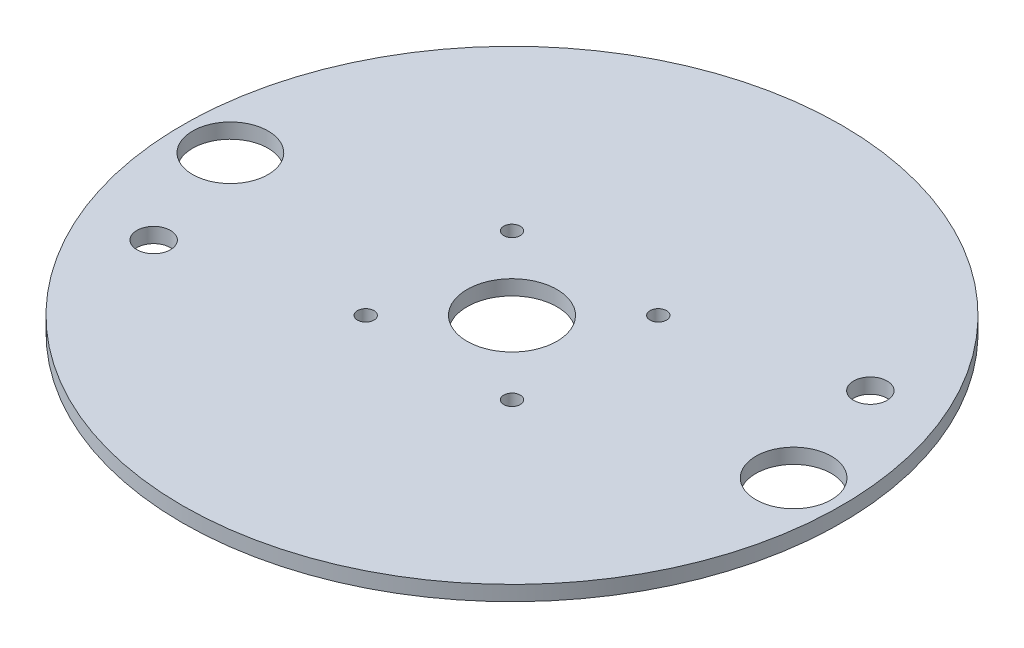
SolidWorks part; units mm, degrees
ref_plane "Front Plane" through (0, 0, 0) normal (0, 0, 1) x (1, 0, 0)
ref_plane "Top Plane" through (0, 0, 0) normal (0, 1, 0) x (1, 0, 0)
ref_plane "Right Plane" through (0, 0, 0) normal (1, 0, 0) x (0, 0, -1)
sketch "Sketch1" plane through (0, 0, 0) normal (0, 1, 0) x (1, 0, 0)
  circle A0 centre (0, 0) radius 69.85
  circle A1 centre (0, 0) radius 9.525
extrude "Boss-Extrude1" add sketch "Sketch1" along normal blind 3.175
sketch "Sketch2" plane through (0, 3.175, 0) normal (0, 1, 0) x (1, 0, 0)
  line L0 (59.69, 0) -> (-59.69, 0) construction
  line L1 (51.7955, 24.1526) -> (-51.7955, -24.1526) construction
  circle A0 centre (-59.69, 0) radius 8.001
  circle A1 centre (59.69, 0) radius 8.001
  circle A2 centre (-51.7955, -24.1526) radius 3.556
  circle A3 centre (51.7955, 24.1526) radius 3.556
  point P5 (0, 0)
  point P9 (0, 0)
extrude "Cut-Extrude1" cut sketch "Sketch2" against normal blind 3.175
sketch "Sketch3" plane through (0, 3.175, 0) normal (0, 1, 0) x (1, 0, 0)
  line L0 (0, -15.5) -> (0, 15.5) construction
  line L1 (15.5, 15.5) -> (-15.5, 15.5) construction
  line L2 (15.5, -15.5) -> (-15.5, -15.5) construction
  circle A0 centre (15.5, 15.5) radius 1.75
  circle A1 centre (15.5, -15.5) radius 1.75
  circle A2 centre (-15.5, -15.5) radius 1.75
  circle A3 centre (-15.5, 15.5) radius 1.75
  point P4 (0, 0)
  point P8 (0, 15.5)
  point P11 (0, -15.5)
extrude "Cut-Extrude2" cut sketch "Sketch3" against normal blind 50.8
